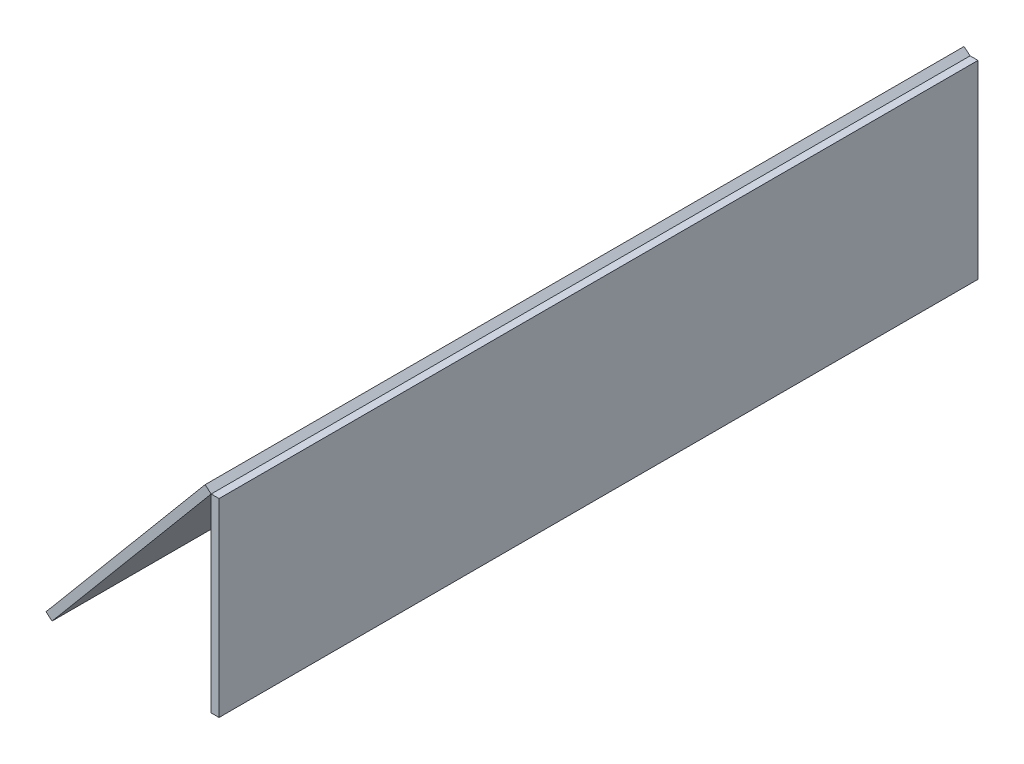
SolidWorks part; units mm, degrees
material "Cedar"
ref_plane "Front Plane" through (0, 0, 0) normal (0, 0, 1) x (1, 0, 0)
ref_plane "Top Plane" through (0, 0, 0) normal (0, 1, 0) x (1, 0, 0)
ref_plane "Right Plane" through (0, 0, 0) normal (1, 0, 0) x (0, 0, -1)
sketch "Sketch1" plane through (0, 0, 0) normal (1, 0, 0) x (0, 0, -1)
  line L1 (-305, -76.2) -> (305, -76.2)
  line L2 (-305, -76.2) -> (-305, 76.2)
  line L3 (-305, 76.2) -> (305, 76.2)
  line L4 (305, -76.2) -> (305, 76.2)
  line L5 (-305, -76.2) -> (305, 76.2) construction
  line L6 (-305, 76.2) -> (305, -76.2) construction
  point P0 (0, 0)
  dimension "D1" = 610
  dimension "D2" = 152.4
extrude "Boss-Extrude1" add sketch "Sketch1" along normal blind 6.35
sketch "Sketch2" plane through (0, 0, -305) normal (0, 0, -1) x (-1, 0, 0)
  line L0 (0, 76.2) -> (127.8788, -76.2)
  line L1 (127.8788, -76.2) -> (132.7432, -72.1183)
  line L2 (132.7432, -72.1183) -> (4.8644, 80.2817)
  line L3 (4.8644, 80.2817) -> (0, 76.2)
  line L4 (-6.35, -76.2) -> (0, -76.2) construction
  line L5 (0, -76.2) -> (0, 76.2) construction
  dimension "D1" = 40
extrude "Boss-Extrude2" add sketch "Sketch2" against normal up to surface (610 mm away) separate body up to face at (3.175, 0, 305)
